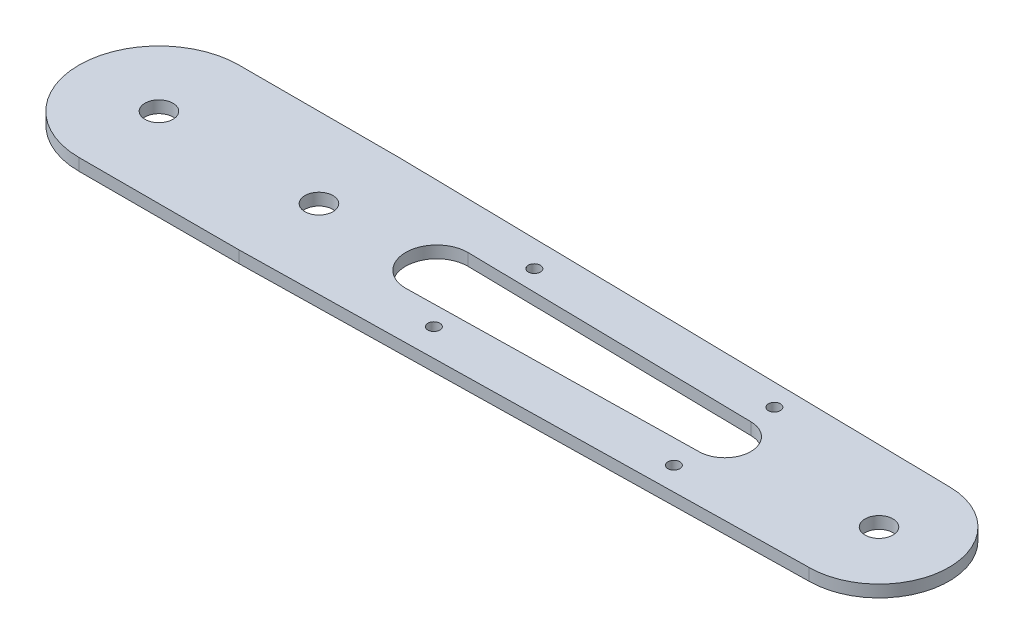
SolidWorks part; units mm, degrees
ref_plane "Front Plane" through (0, 0, 0) normal (0, 0, 1) x (1, 0, 0)
ref_plane "Top Plane" through (0, 0, 0) normal (0, 1, 0) x (1, 0, 0)
ref_plane "Right Plane" through (0, 0, 0) normal (1, 0, 0) x (0, 0, -1)
sketch "Sketch1" plane through (0, 0, 0) normal (0, 1, 0) x (1, 0, 0)
  line L0 (0.3571, 19.9968) -> (140.3125, 17.4972)
  line L1 (140, -17.5) -> (0, -20)
  circle A0 centre (0, 0) radius 20
  circle A1 centre (140, 0) radius 17.5
  point P11 (70.9941, 1.1797)
  dimension "D1" = 140
  dimension "D2" = 40
  dimension "D3" = 35
extrude "Boss-Extrude1" add sketch "Sketch1" along normal blind 3 contours L1 A0 | A1 L0 A0 L1 | A1 A0
sketch "Sketch2" plane through (0, 3, 0) normal (0, 1, 0) x (1, 0, 0)
  circle A0 centre (0, 0) radius 3.5
  circle A1 centre (140, 0) radius 3.5
  dimension "D1" = 7
  dimension "D2" = 7
extrude "Cut-Extrude1" cut sketch "Sketch2" against normal through all
sketch "Sketch4" plane through (0, 3, 0) normal (0, 1, 0) x (1, 0, 0)
  line L0 (101.2839, 6.7707) -> (29.173, 8.0586)
  line L1 (29.1576, -7.4774) -> (101.4946, -6.1857)
  arc A6 (29.173, 8.0586) -> (29.1576, -7.4774) centre (29.1653, 0.2906) ccw
  arc A7 (101.2839, 6.7707) -> (101.0524, -6.1936) centre (101.1578, 0.2888) cw
  dimension "D2" = 7.768
  dimension "D3" = 6.4832
  dimension "D1" = 72.337
  dimension "D4" = 2.046
extrude "Cut-Extrude3" cut sketch "Sketch4" against normal through all contours A7 L0 A6 L1
sketch "Sketch9" plane through (0, 3, 0) normal (0, 1, 0) x (1, 0, 0)
  circle A0 centre (140, 0) radius 3.517
sketch "Sketch10" plane through (0, 3, 0) normal (0, 1, 0) x (1, 0, 0)
  line L0 (0.3571, 19.9968) -> (-40, 20)
  line L1 (-40, -20) -> (0, -20)
  circle A0 centre (-40, 0) radius 3.5
  arc A1 (-39.9984, 20) -> (-40, -20) centre (-40, 0) ccw
  arc A3 (0.3571, 19.9968) -> (0, -20) centre (0, 0) ccw
  arc M9 (0.3571, 19.9968) -> (0, -20) centre (0, 0) ccw
  dimension "D1" = 7
  dimension "D3" = 40
  dimension "D2" = 40
extrude "Boss-Extrude2" add sketch "Sketch10" against normal blind 3 contours L0 A1 L1 A0 M9
sketch "Sketch11" plane through (0, 3, 0) normal (0, 1, 0) x (1, 0, 0)
  line L0 (70.9941, 1.1797) -> (70.9941, 42.412) construction
  line L1 (101.2839, 6.7707) -> (29.173, 8.0586) construction
  line L2 (29.1576, -7.4774) -> (101.4946, -6.1857) construction
  circle A0 centre (40.9941, 12.8483) radius 1.5
  circle A1 centre (40.9941, -12.2668) radius 1.5
  circle A2 centre (100.9941, -12.2668) radius 1.5
  circle A3 centre (100.9941, 12.8483) radius 1.5
  dimension "D1" = 3
  dimension "D3" = 30
  dimension "D2" = 5
  dimension "D4" = 5
extrude "Cut-Extrude4" cut sketch "Sketch11" against normal blind 10
